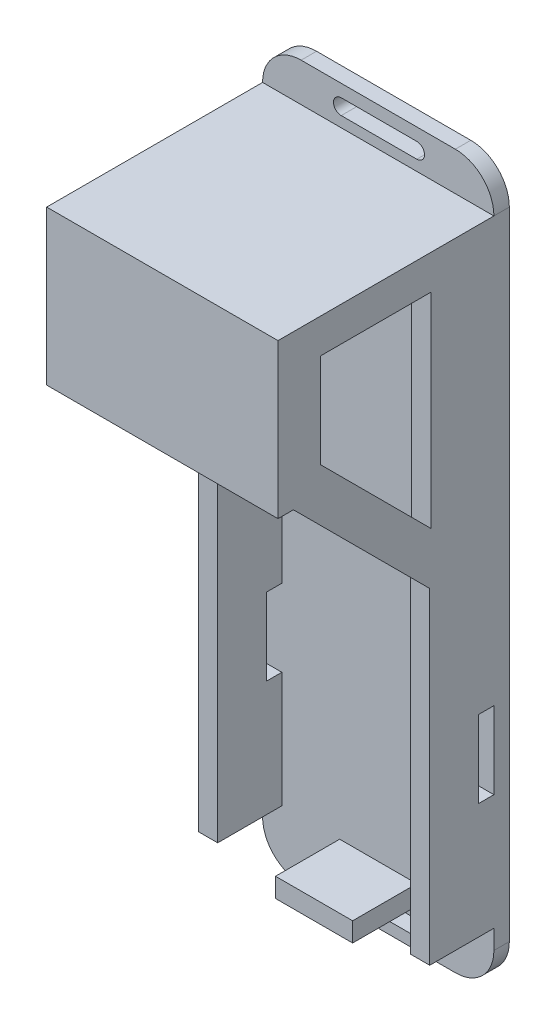
SolidWorks part; units mm, degrees
ref_plane "Alzado" through (0, 0, 0) normal (0, 0, 1) x (1, 0, 0)
ref_plane "Planta" through (0, 0, 0) normal (0, 1, 0) x (1, 0, 0)
ref_plane "Vista lateral" through (0, 0, 0) normal (1, 0, 0) x (0, 0, -1)
sketch "Croquis1" plane through (0, 0, 0) normal (0, 0, 1) x (1, 0, 0)
  line L0 (0, -77.5) -> (10, -77.5)
  line L1 (-20, -92.5) -> (20, -92.5)
  line L2 (-30, -82.5) -> (-30, 82.5)
  line L3 (-20, 92.5) -> (20, 92.5)
  line L4 (30, -82.5) -> (30, 82.5)
  line L5 (-30, -92.5) -> (30, 92.5) construction
  line L6 (-30, 92.5) -> (30, -92.5) construction
  line L7 (-25, -77.5) -> (25, -77.5)
  line L8 (-25, -77.5) -> (-25, 77.5)
  line L9 (-25, 77.5) -> (25, 77.5)
  line L10 (25, -77.5) -> (25, 77.5)
  line L11 (-25, -77.5) -> (25, 77.5) construction
  line L12 (-25, 77.5) -> (25, -77.5) construction
  line L13 (10, -77.5) -> (10, -82.5)
  line L14 (10, -82.5) -> (-10, -82.5)
  line L15 (-10, -82.5) -> (-10, -77.5)
  line L16 (-10, -77.5) -> (0, -77.5)
  line L17 (-25, -77.5) -> (-30, -77.5)
  line L18 (-30, -77.5) -> (-30, 82.5)
  line L19 (30, 82.5) -> (-30, 82.5)
  line L20 (25, -77.5) -> (30, -77.5)
  line L21 (30, -77.5) -> (30, 82.5)
  arc A0 (-20, -92.5) -> (-30, -82.5) centre (-20, -82.5) cw
  arc A1 (20, -92.5) -> (30, -82.5) centre (20, -82.5) ccw
  arc A2 (20, 92.5) -> (30, 82.5) centre (20, 82.5) cw
  arc A3 (-30, 82.5) -> (-20, 92.5) centre (-20, 82.5) cw
  point P0 (0, 0)
  point P6 (0, 0)
  dimension "D5" = 10
  dimension "D1" = 60
  dimension "D2" = 185
  dimension "D3" = 50
  dimension "D4" = 155
extrude "Saliente-Extruir2" add sketch "Croquis1" along normal blind 4 contours A3 L19 A2 L3 | L10 L20 L4 L19 L2 L17 L8 L9 | L7 L10 L9 L8 L0 | L1 A1 L4 L20 L7 L13 L14 L15 L17 L2 A0 | L15 L14 L13 L0 L7
sketch "Croquis2" plane through (0, 0, 4) normal (0, 0, 1) x (1, 0, 0)
  line L0 (0, -77.5) -> (10, -77.5)
  line L1 (-20, -92.5) -> (20, -92.5)
  line L2 (-30, -82.5) -> (-30, 82.5)
  line L3 (-20, 92.5) -> (20, 92.5)
  line L4 (30, -82.5) -> (30, 82.5)
  line L5 (-30, -92.5) -> (30, 92.5) construction
  line L6 (-30, 92.5) -> (30, -92.5) construction
  line L7 (-25, -77.5) -> (25, -77.5)
  line L8 (-25, -77.5) -> (-25, 77.5)
  line L9 (-25, 77.5) -> (25, 77.5)
  line L10 (25, -77.5) -> (25, 77.5)
  line L11 (-25, -77.5) -> (25, 77.5) construction
  line L12 (-25, 77.5) -> (25, -77.5) construction
  line L13 (10, -77.5) -> (10, -82.5)
  line L14 (10, -82.5) -> (-10, -82.5)
  line L15 (-10, -82.5) -> (-10, -77.5)
  line L16 (-10, -77.5) -> (0, -77.5)
  line L17 (-25, -77.5) -> (-30, -77.5)
  line L18 (-30, -77.5) -> (-30, 82.5)
  line L19 (30, 82.5) -> (-30, 82.5)
  line L20 (25, -77.5) -> (30, -77.5)
  line L21 (30, -77.5) -> (30, 82.5)
  line L22 (-20, -92.5) -> (20, -92.5) construction
  line L23 (30, -82.5) -> (30, 82.5) construction
  arc A0 (-20, -92.5) -> (-30, -82.5) centre (-20, -82.5) cw
  arc A1 (20, -92.5) -> (30, -82.5) centre (20, -82.5) ccw
  arc A2 (20, 92.5) -> (30, 82.5) centre (20, 82.5) cw
  arc A3 (-30, 82.5) -> (-20, 92.5) centre (-20, 82.5) cw
  point P0 (0, 0)
  point P5 (0, 0)
  line M16 (-30, 82.5) -> (-30, -82.5)
  dimension "D5" = 10
  dimension "D1" = 60
  dimension "D2" = 185
  dimension "D3" = 50
  dimension "D4" = 155
  dimension "D6" = 0
  dimension "D7" = 0
extrude "Saliente-Extruir3" add sketch "Croquis2" along normal blind 52 contours L15 L14 L13 L0 L7 | L10 L20 L4 L19 L17 L8 L9 M16
sketch "Croquis3" plane through (0, 82.5, 0) normal (0, 1, 0) x (1, 0, 0)
  line L1 (30, -56) -> (-30, -56)
  line L2 (30, -56) -> (30, -60)
  line L3 (30, -60) -> (-30, -60)
  line L4 (-30, -56) -> (-30, -60)
  dimension "D1" = 4
extrude "Saliente-Extruir4" add sketch "Croquis3" against normal blind 40
sketch "Croquis4" plane through (-30, 0, 0) normal (-1, 0, 0) x (0, 0, 1)
  line L0 (56, 42.5) -> (20.6447, 7.1447)
  line L1 (20.6447, 7.1447) -> (20.6447, -100.0885)
  line L2 (20.6447, -100.0885) -> (56, -100.0885)
  line L3 (56, -100.0885) -> (56, 42.5)
extrude "Cortar-Extruir1" cut sketch "Croquis4" against normal blind 87
sketch "Croquis6" plane through (25, 0, 0) normal (-1, 0, 0) x (0, 0, 1)
  line L0 (4, -77.5) -> (4, 77.5) construction
  line L1 (4, -47.5) -> (8, -47.5)
  line L2 (4, -47.5) -> (4, -27.5)
  line L3 (4, -27.5) -> (8, -27.5)
  line L4 (8, -47.5) -> (8, -27.5)
  line L5 (20.6447, -77.5) -> (4, -77.5) construction
  dimension "D1" = 20
  dimension "D2" = 30
  dimension "D3" = 4
extrude "Cortar-Extruir2" cut sketch "Croquis6" against normal blind 87 and the other way blind 87
sketch "Croquis7" plane through (-30, 0, 0) normal (-1, 0, 0) x (0, 0, 1)
  line L1 (20.3254, 20.468) -> (20.3254, 73.5459)
  line L2 (20.3254, 73.5459) -> (48.9908, 73.5459)
  line L4 (48.9908, 73.5459) -> (48.9908, 49.1334)
  line L5 (48.9908, 49.1334) -> (20.3254, 20.468)
  dimension "D1" = 90
  dimension "D2" = 45
extrude "Cortar-Extruir3" cut sketch "Croquis7" against normal blind 87
sketch "Croquis8" plane through (0, 0, 4) normal (0, 0, 1) x (1, 0, 0)
  line L0 (-9.6022, -87.5) -> (10, -87.5) construction
  line L1 (-9.6022, -85.5) -> (10, -85.5)
  line L2 (-9.6022, -89.5) -> (10, -89.5)
  line L3 (10, -77.5) -> (10, -82.5) construction
  line L4 (10, 87.25) -> (-9.6022, 87.25) construction
  line L5 (10, 85.25) -> (-9.6022, 85.25)
  line L6 (10, 89.25) -> (-9.6022, 89.25)
  line L7 (-20, 92.5) -> (20, 92.5) construction
  line L8 (-20, -92.5) -> (20, -92.5) construction
  arc A0 (-9.6022, -85.5) -> (-9.6022, -89.5) centre (-9.6022, -87.5) ccw
  arc A1 (10, -89.5) -> (10, -85.5) centre (10, -87.5) ccw
  arc A2 (10, 85.25) -> (10, 89.25) centre (10, 87.25) ccw
  arc A3 (-9.6022, 89.25) -> (-9.6022, 85.25) centre (-9.6022, 87.25) ccw
  point P2 (0.1989, -87.5)
  point P11 (0.1989, 87.25)
  dimension "D2" = 2
  dimension "D3" = 2
  dimension "D1" = 0
  dimension "D4" = 3.25
  dimension "D5" = 3
extrude "Cortar-Extruir4" cut sketch "Croquis8" against normal blind 87
